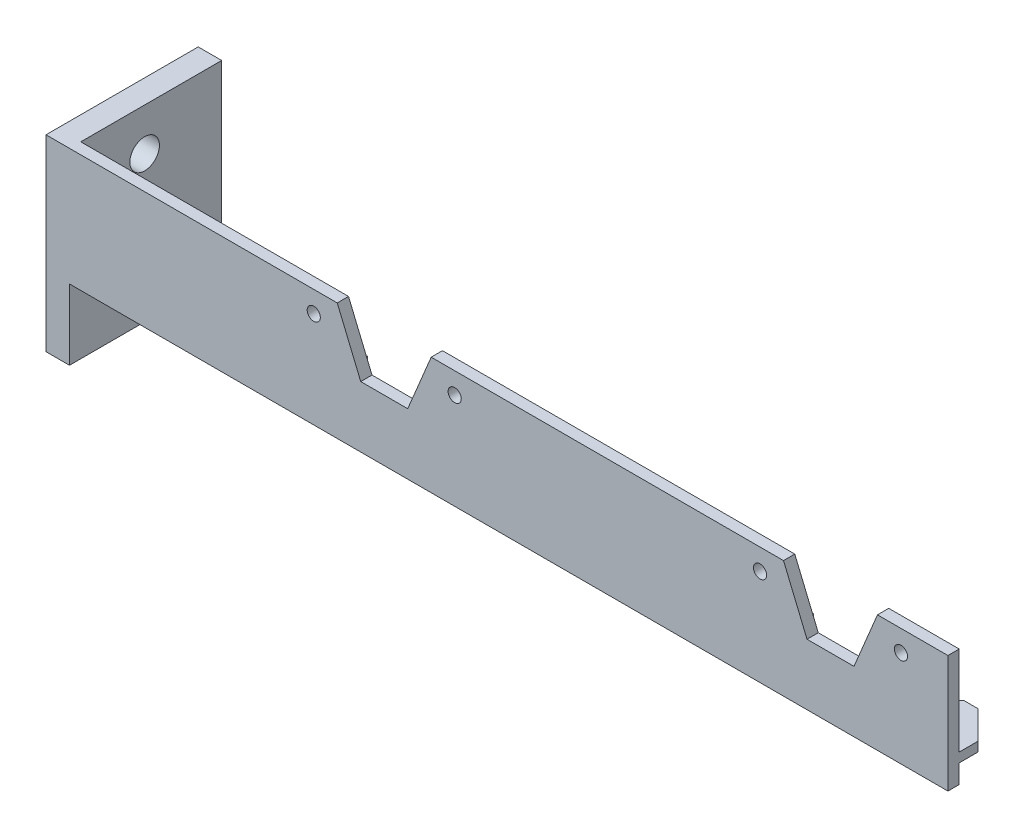
SolidWorks part; units mm, degrees
ref_plane "Front Plane" through (0, 0, 0) normal (0, 0, 1) x (1, 0, 0)
ref_plane "Top Plane" through (0, 0, 0) normal (0, 1, 0) x (1, 0, 0)
ref_plane "Right Plane" through (0, 0, 0) normal (1, 0, 0) x (0, 0, -1)
sketch "Sketch1" plane through (0, 0, 0) normal (0, 0, 1) x (1, 0, 0)
  line L1 (0, 0) -> (192, 0)
  line L2 (0, 0) -> (0, 25)
  line L3 (0, 25) -> (192, 25)
  line L4 (192, 0) -> (192, 25)
  dimension "D1" = 192
  dimension "D2" = 25
extrude "Boss-Extrude1" add sketch "Sketch1" along normal blind 2.4
sketch "Sketch2" plane through (0, 0, 2.4) normal (0, 0, 1) x (1, 0, 0)
  line L0 (72, 25) -> (72, 0) construction
  line L1 (192, 25) -> (0, 25) construction
  line L2 (0, 0) -> (192, 0) construction
  line L3 (167, 25) -> (167, 0) construction
  line L4 (192, 0) -> (192, 25) construction
  line L5 (177, 25) -> (172, 13)
  line L6 (172, 13) -> (162, 13)
  line L7 (157, 25) -> (162, 13)
  line L8 (82, 25) -> (77, 13)
  line L9 (77, 13) -> (67, 13)
  line L10 (62, 25) -> (67, 13)
  line L11 (62, 25) -> (82, 25)
  line L12 (157, 25) -> (177, 25)
  line L13 (0, 20.5) -> (192, 20.5) construction
  line L14 (0, 25) -> (0, 0) construction
  circle A0 centre (87, 20.5) radius 1.4
  circle A1 centre (57, 20.5) radius 1.4
  circle A2 centre (152, 20.5) radius 1.4
  circle A3 centre (182, 20.5) radius 1.4
  point P14 (167, 13)
  point P19 (72, 13)
  dimension "D10" = 2.8
  dimension "D2" = 72
  dimension "D3" = 5
  dimension "D4" = 10
  dimension "D5" = 5
  dimension "D6" = 10
  dimension "D7" = 12
  dimension "D8" = 12
  dimension "D9" = 7.5
  dimension "D11" = 15
  dimension "D12" = 15
  dimension "D13" = 15
  dimension "D14" = 167
extrude "Cut-Extrude1" cut sketch "Sketch2" against normal through all
sketch "Sketch3" plane through (0, 0, 0) normal (0, 0, -1) x (-1, 0, 0)
  line L0 (0, 25) -> (0, 0) construction
  line L1 (-5, 25) -> (0, 25)
  line L2 (-5, 25) -> (-5, -15)
  line L3 (-5, -15) -> (0, -15)
  line L4 (0, 25) -> (0, -15)
  line L5 (-192, 25) -> (-177, 25) construction
  line L6 (0, 0) -> (-192, 0) construction
  dimension "D1" = 5
  dimension "D2" = 40
extrude "Boss-Extrude2" add sketch "Sketch3" along normal blind 30 and the other way up to surface other way up to face at (183.4, 20.5, 2.4)
sketch "Sketch4" plane through (0, 0, 0) normal (-1, 0, 0) x (0, 0, 1)
  line L0 (-13.6, 25) -> (-13.6, -15) construction
  line L1 (-30, 25) -> (2.4, 25) construction
  line L2 (-30, -15) -> (2.4, -15) construction
  line L3 (2.4, 0) -> (2.4, 25) construction
  circle A0 centre (-13.6, 16) radius 3.15
  circle A1 centre (-13.6, -6) radius 3.15
  dimension "D2" = 6.3
  dimension "D4" = 6.3
  dimension "D1" = 16
  dimension "D3" = 9
  dimension "D5" = 9
extrude "Cut-Extrude2" cut sketch "Sketch4" against normal blind 30
sketch "Sketch7" [suppressed] plane through (0, 0, 0) normal (-1, 0, 0) x (0, 0, 1)
  line L0 (-2, 0) -> (0, 15)
  line L1 (0, 15) -> (-5.2606, 15)
  line L2 (-5.2606, 15) -> (-2, 0)
extrude "Cut-Extrude3" [suppressed] cut sketch "Sketch7" against normal up to surface (144 mm away)
chamfer "Chamfer2" [suppressed] distance 2 angle 45
fillet "Fillet2" [suppressed] radius 2
chamfer "Chamfer3" [suppressed] distance 3 angle 15
chamfer "Chamfer4" [suppressed] distance 2 angle 79
sketch "Sketch8" plane through (5, 0, 0) normal (1, 0, 0) x (0, 0, -1)
  line L0 (30, 5) -> (0, 5) construction
  line L1 (30, 25) -> (30, -15) construction
  line L2 (0, 25) -> (0, 0) construction
  line L4 (10, 6) -> (0, 6)
  line L5 (10, 6) -> (10, 4)
  line L6 (10, 4) -> (0, 4)
  line L7 (0, 6) -> (0, 4)
  line L8 (10, 6) -> (0, 4) construction
  line L9 (10, 4) -> (0, 6) construction
  point P6 (5, 5)
  dimension "D1" = 2
  dimension "D2" = 10
extrude "Boss-Extrude4" add sketch "Sketch8" along normal up to surface (187 mm away) up to face at (192, 12.5, 1.2)
sketch "Sketch9" plane through (0, 25, 0) normal (0, 1, 0) x (1, 0, 0)
  line L0 (62, 0) -> (62, 13.8573)
  line L1 (62, 13.8573) -> (82, 13.8573)
  line L2 (82, 13.8573) -> (82, 0)
  line L3 (82, 0) -> (62, 0)
  line L4 (177, 0) -> (177, 13.8573)
  line L5 (177, 13.8573) -> (157, 13.8573)
  line L6 (157, 13.8573) -> (157, 0)
  line L7 (157, 0) -> (177, 0)
  line L8 (157, 0) -> (157, -2.4) construction
  line L9 (82, 0) -> (82, -2.4) construction
extrude "Cut-Extrude4" cut sketch "Sketch9" against normal through all
chamfer "Chamfer5" distance 6 angle 45 5 edges at (177, 5, -10) (82, 5, -10) (157, 5, -10) (62, 5, -10) (192, 5, -10)
